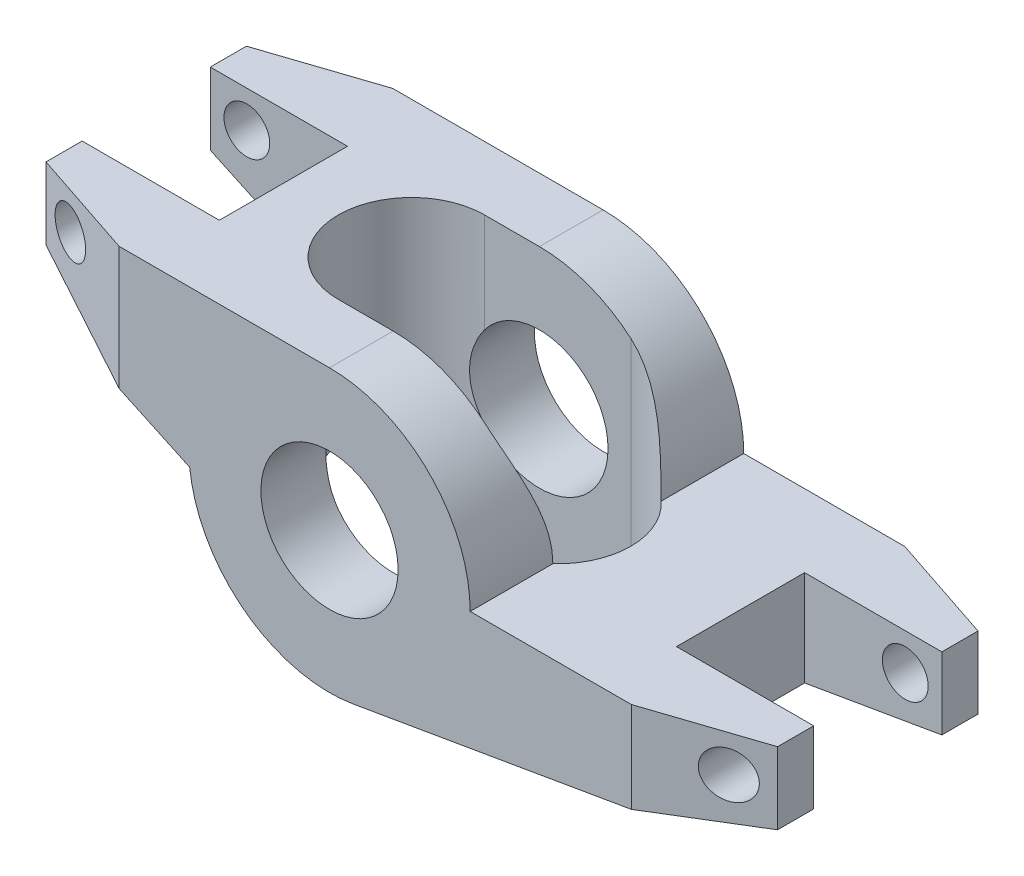
SolidWorks part; units mm, degrees
ref_plane "Front Plane" through (0, 0, 0) normal (0, 0, 1) x (1, 0, 0)
ref_plane "Top Plane" through (0, 0, 0) normal (0, 1, 0) x (1, 0, 0)
ref_plane "Right Plane" through (0, 0, 0) normal (1, 0, 0) x (0, 0, -1)
sketch "Sketch1" plane through (0, 0, 0) normal (0, 0, 1) x (1, 0, 0)
  line L0 (0, 9.77) -> (-22.23, 9.77)
  line L1 (-22.23, 9.77) -> (-22.23, 4.77)
  line L2 (-22.23, 4.77) -> (-9.7115, -1.0675)
  line L3 (9.77, 0) -> (28.58, 0)
  line L4 (28.58, 0) -> (28.58, -5)
  line L5 (28.58, -5) -> (1.6553, -9.6287)
  arc A0 (-9.7115, -1.0675) -> (1.6553, -9.6287) centre (0, 0) ccw
  circle A1 centre (0, 0) radius 4.765
  arc A2 (9.77, 0) -> (0, 9.77) centre (0, 0) ccw
  dimension "D1" = 19.54
  dimension "D2" = 9.53
  dimension "D3" = 22.23
  dimension "D4" = 5
  dimension "D5" = 25
  dimension "D6" = 28.58
extrude "Boss-Extrude1" add sketch "Sketch1" along normal mid plane 19
chamfer "Chamfer1" distance 7.62 distance2 2.54 2 edges at (28.58, -2.5, -9.5) (-22.23, 7.27, -9.5)
chamfer "Chamfer2" distance 2.54 distance2 7.62 2 edges at (-22.23, 7.27, 9.5) (28.58, -2.5, 9.5)
sketch "Sketch2" plane through (0, 0, 0) normal (0, 1, 0) x (1, 0, 0)
  line L0 (-22.23, -6.96) -> (-22.23, 6.96) construction
  line L1 (-22.23, 4.45) -> (-12.7, 4.45)
  line L2 (-22.23, 4.45) -> (-22.23, -4.45)
  line L3 (-22.23, -4.45) -> (-12.7, -4.45)
  line L4 (-12.7, 4.45) -> (-12.7, -4.45)
  line L5 (28.58, -6.96) -> (28.58, 6.96) construction
  line L6 (28.58, 4.45) -> (19.05, 4.45)
  line L7 (28.58, 4.45) -> (28.58, -4.45)
  line L8 (28.58, -4.45) -> (19.05, -4.45)
  line L9 (19.05, 4.45) -> (19.05, -4.45)
  point P12 (-12.7, 0)
  point P14 (19.05, 0)
  dimension "D1" = 9.53
  dimension "D2" = 8.9
extrude "Cut-Extrude1" cut sketch "Sketch2" against normal through all both and the other way through all
sketch "Sketch3" plane through (0, 0, 0) normal (0, 1, 0) x (1, 0, 0)
  line L0 (-3.81, 0) -> (6.35, 0) construction
  line L1 (-3.81, 5.08) -> (6.35, 5.08)
  line L2 (-3.81, -5.08) -> (6.35, -5.08)
  line L3 (-12.7, -4.45) -> (-12.7, 4.45) construction
  arc A0 (-3.81, 5.08) -> (-3.81, -5.08) centre (-3.81, 0) ccw
  arc A1 (6.35, -5.08) -> (6.35, 5.08) centre (6.35, 0) ccw
  point P3 (1.27, 0)
  dimension "D2" = 5.08
  dimension "D1" = 8.89
  dimension "D3" = 10.16
extrude "Cut-Extrude2" cut sketch "Sketch3" against normal through all both and the other way through all
sketch "Sketch4" plane through (0, 0, 0) normal (0, 0, 1) x (1, 0, 0)
  line L0 (-22.23, 4.77) -> (-22.23, 9.77) construction
  line L1 (-22.23, 9.77) -> (-14.61, 9.77) construction
  line L2 (28.58, 0) -> (28.58, -5) construction
  line L3 (20.96, 0) -> (28.58, 0) construction
  circle A0 centre (-19.69, 7.23) radius 1.59
  circle A1 centre (26.04, -2.54) radius 1.59
  point P4 (0, 0)
  dimension "D1" = 3.18
  dimension "D2" = 2.54
  dimension "D3" = 2.54
  dimension "D4" = 2.54
  dimension "D5" = 2.54
extrude "Cut-Extrude3" cut sketch "Sketch4" against normal through all both and the other way through all
